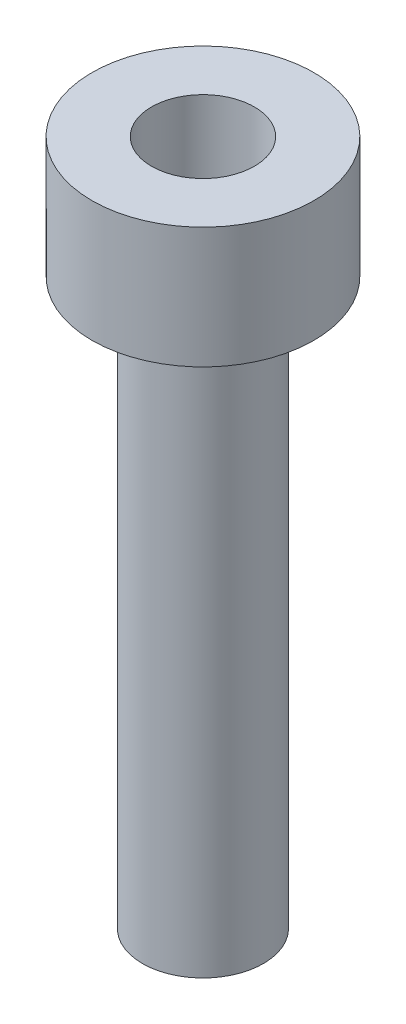
SolidWorks part; units mm, degrees
material "Alloy Steel"
ref_plane "Front Plane" through (0, 0, 0) normal (0, 0, 1) x (1, 0, 0)
ref_plane "Top Plane" through (0, 0, 0) normal (0, 1, 0) x (1, 0, 0)
ref_plane "Right Plane" through (0, 0, 0) normal (1, 0, 0) x (0, 0, -1)
other "Configuration Table"
sketch "Sketch1" plane through (0, 0, 0) normal (0, 1, 0) x (1, 0, 0)
  circle A0 centre (0, 0) radius 2.75
  dimension "D1" = 5.5
extrude "Head" add sketch "Sketch1" along normal blind 3
sketch "Sketch2" plane through (0, 0, 0) normal (0, 1, 0) x (1, 0, 0)
  circle A0 centre (0, 0) radius 1.5
  dimension "D1" = 3
extrude "Shank" add sketch "Sketch2" along normal blind 14 from offset 14
sketch "Sketch3" plane through (0, 0, 0) normal (0, 1, 0) x (1, 0, 0)
  circle A0 centre (0, 0) radius 1.275
  dimension "D1" = 2.55
extrude "Socket" cut sketch "Sketch3" against normal blind 1.8 from offset 3
equation "\"Jar_OD\"= 90  'ASSUMED - Part G fallback - jar outer diameter"
equation "\"Jar_H\"= 120  'ASSUMED - Part G fallback - jar height"
equation "\"Pump_L\"= 45  'ASSUMED - Part G fallback"
equation "\"Pump_W\"= 24  'ASSUMED - Part G fallback"
equation "\"Pump_H\"= 33  'ASSUMED - Part G fallback"
equation "\"Pump_Outlet_OD\"= 7.5  'ASSUMED - Part G fallback"
equation "\"Tube_OD\"= 8  'ASSUMED - Part G fallback"
equation "\"Tube_ID\"= 6  'ASSUMED - Part G fallback"
equation "\"TDS_Body_Dia\"= 12  'ASSUMED - Part G fallback"
equation "\"TDS_Wet_Len\"= 45  'ASSUMED - Part G fallback - length in water"
equation "\"DS_Tube_Dia\"= 6  'ASSUMED - Part G fallback"
equation "\"DS_Tube_Len\"= 50  'ASSUMED - Part G fallback"
equation "\"ORP_Body_Dia\"= 12  'ASSUMED - Part G fallback"
equation "\"ORP_Body_Len\"= 150  'ASSUMED - Part G fallback"
equation "\"ORP_Cap_Dia\"= 16  'ASSUMED - Part G fallback"
equation "\"Turb_W\"= 33  'ASSUMED - Part G fallback - head width"
equation "\"Turb_D\"= 28  'ASSUMED - Part G fallback - head depth"
equation "\"Turb_H\"= 30  'ASSUMED - Part G fallback - head height"
equation "\"Turb_Slot_W\"= 10  'ASSUMED - Part G fallback - slot width"
equation "\"Flow_L\"= 62  'ASSUMED - Part G fallback YF-S201"
equation "\"Flow_W\"= 36  'ASSUMED - Part G fallback"
equation "\"Flow_H\"= 35  'ASSUMED - Part G fallback"
equation "\"Thread_G12_OD\"= 20.955  'ASSUMED - Part G fallback thread G1/2 (major diameter)"
equation "\"Valve_L\"= 75  'ASSUMED - Part G fallback"
equation "\"Valve_W\"= 45  'ASSUMED - Part G fallback"
equation "\"Valve_H\"= 60  'ASSUMED - Part G fallback"
equation "\"Tee_L\"= 40  'ASSUMED - Part G fallback - overall length"
equation "\"Tee_Branch_L\"= 25  'ASSUMED - Part G fallback"
equation "\"Tee_OD\"= 12  'ASSUMED - Part G fallback"
equation "\"Cuv_W\"= 12.5  'ASSUMED - old R3 cuvette (station suppressed in SS4)"
equation "\"Cuv_D\"= 12.5  'ASSUMED - old R3 cuvette (station suppressed in SS4)"
equation "\"Cuv_H\"= 45  'ASSUMED - old R3 cuvette (station suppressed in SS4)"
equation "\"LED_Board_L\"= 20  'ASSUMED - Part G fallback"
equation "\"LED_Board_W\"= 20  'ASSUMED - Part G fallback - LED at centre"
equation "\"GUVA_L\"= 20  'ASSUMED - Part G fallback"
equation "\"GUVA_W\"= 12  'ASSUMED - Part G fallback - sensor at centre"
equation "\"Reed_L\"= 27  'ASSUMED - Part G fallback MC-38 half"
equation "\"Reed_W\"= 14  'ASSUMED - Part G fallback"
equation "\"Reed_H\"= 8  'ASSUMED - Part G fallback"
equation "\"ESP_L\"= 51  'ASSUMED - Part G fallback"
equation "\"ESP_W\"= 28  'ASSUMED - Part G fallback"
equation "\"TFT_L\"= 58  'ASSUMED - Part G fallback - board"
equation "\"TFT_W\"= 35  'ASSUMED - Part G fallback - board"
equation "\"TFT_Win_L\"= 35  'ASSUMED - Part G fallback - visible window"
equation "\"TFT_Win_W\"= 28  'ASSUMED - Part G fallback - visible window"
equation "\"Relay_L\"= 50  'ASSUMED - Part G fallback"
equation "\"Relay_W\"= 26  'ASSUMED - Part G fallback"
equation "\"Relay_H\"= 19  'ASSUMED - Part G fallback"
equation "\"Mosfet_L\"= 34  'ASSUMED - Part G fallback"
equation "\"Mosfet_W\"= 17  'ASSUMED - Part G fallback"
equation "\"Mosfet_H\"= 12  'ASSUMED - Part G fallback"
equation "\"TDS_Board_L\"= 42  'ASSUMED - Part G fallback"
equation "\"TDS_Board_W\"= 32  'ASSUMED - Part G fallback"
equation "\"Turb_Board_L\"= 38  'ASSUMED - Part G fallback"
equation "\"Turb_Board_W\"= 28  'ASSUMED - Part G fallback"
equation "\"BNC_Thread_Dia\"= 9.5  'ASSUMED - Part G fallback"
equation "\"Plate_L\"= 420  'ASSUMED - Part G fallback"
equation "\"Plate_W\"= 297  'ASSUMED - Part G fallback"
equation "\"Plate_T\"= 6  'ASSUMED - Part G fallback"
equation "\"Probe_Clr\"= 0.3  'DESIGN VALUE - Part C rule 3 - printed probe hole = diameter + 0.3"
equation "\"Cuv_Clr\"= 0.2  'DESIGN VALUE - Part C rule 3 - cuvette pocket = size + 0.2"
equation "\"Label_H\"= 0.6  'DESIGN VALUE - Part D - raised label height"
equation "\"Booster_L\"= 150  'ASSUMED - Part G fallback - booster pump"
equation "\"Booster_W\"= 95  'ASSUMED - Part G fallback"
equation "\"Booster_H\"= 100  'ASSUMED - Part G fallback"
equation "\"PTube_OD\"= 6.35  'ASSUMED - Part G fallback - product tube 1/4 inch"
equation "\"Qz_Out\"= 12  'ASSUMED - Part G fallback - quartz channel outside square"
equation "\"Qz_Path\"= 10  'ASSUMED - Part G fallback - quartz channel inside light path"
equation "\"Qz_L\"= 40  'ASSUMED - Part G fallback - quartz channel length"
equation "\"LED860_Dia\"= 5  'ASSUMED - Part G fallback - 860 nm LED"
equation "\"BPW_L\"= 5.4  'ASSUMED - Part G fallback - BPW34"
equation "\"BPW_W\"= 4.3  'ASSUMED - Part G fallback - BPW34"
equation "\"Cart_Dia\"= 50  'ASSUMED - Part G fallback - sediment and pre-carbon cartridges"
equation "\"Cart_L\"= 255  'ASSUMED - Part G fallback"
equation "\"UF_Dia\"= 50  'ASSUMED - Part G fallback - UF cartridge"
equation "\"UF_L\"= 260  'ASSUMED - Part G fallback"
equation "\"RO_Dia\"= 62  'ASSUMED - Part G fallback - RO membrane housing"
equation "\"RO_L\"= 300  'ASSUMED - Part G fallback"
equation "\"UVC_Dia\"= 40  'ASSUMED - Part G fallback - UV-C chamber"
equation "\"UVC_L\"= 300  'ASSUMED - Part G fallback"
equation "\"Tank_W\"= 260  'ASSUMED - Part G fallback - storage tank"
equation "\"Tank_D\"= 160  'ASSUMED - Part G fallback"
equation "\"Tank_H\"= 300  'ASSUMED - Part G fallback"
equation "\"Cab_W\"= 400  'ASSUMED - Part G fallback - purifier cabinet"
equation "\"Cab_D\"= 270  'ASSUMED - Part G fallback"
equation "\"Cab_H\"= 560  'ASSUMED - Part G fallback"
equation "\"ORP_Board_L\"= 40  'ASSUMED - Part G fallback - ORP buffer board"
equation "\"ORP_Board_W\"= 30  'ASSUMED - Part G fallback"
equation "\"Opt_Board_L\"= 50  'ASSUMED - Part G fallback - optical front-end board"
equation "\"Opt_Board_W\"= 40  'ASSUMED - Part G fallback"
equation "\"Buck_L\"= 43  'ASSUMED - Part G fallback - 12 V to 5 V buck module"
equation "\"Buck_W\"= 21  'ASSUMED - Part G fallback"
equation "\"Buck_H\"= 14  'ASSUMED - Part G fallback"
equation "\"BB_L\"= 165  'ASSUMED - Part G fallback - breadboard (As_Built_R3 only)"
equation "\"BB_W\"= 55  'ASSUMED - Part G fallback"
equation "\"BB_H\"= 10  'ASSUMED - Part G fallback"
